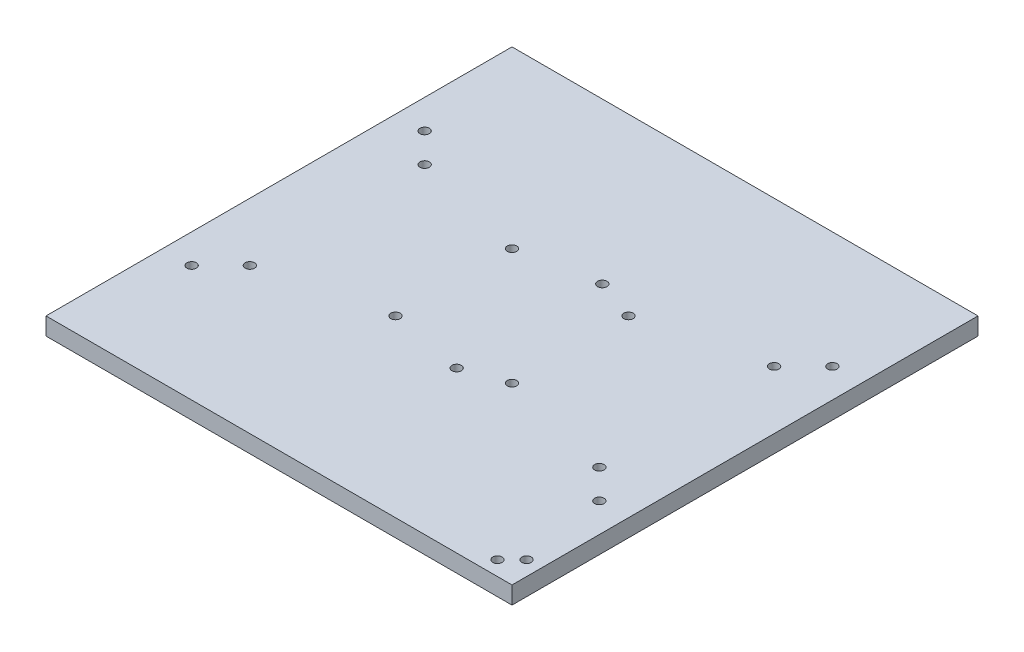
SolidWorks part; units mm, degrees
ref_plane "Alzado" through (0, 0, 0) normal (0, 0, 1) x (1, 0, 0)
ref_plane "Planta" through (0, 0, 0) normal (0, 1, 0) x (1, 0, 0)
ref_plane "Vista lateral" through (0, 0, 0) normal (1, 0, 0) x (0, 0, -1)
sketch "Croquis1" plane through (0, 0, 0) normal (0, 1, 0) x (1, 0, 0)
  line L1 (-80, 80) -> (80, 80)
  line L2 (-80, 80) -> (-80, -80)
  line L3 (-80, -80) -> (80, -80)
  line L4 (80, 80) -> (80, -80)
  line L5 (-80, 80) -> (80, -80) construction
  line L6 (-80, -80) -> (80, 80) construction
  line L7 (-60, 30) -> (60, 30) construction
  line L8 (-60, 30) -> (-60, -30) construction
  line L9 (-60, -30) -> (60, -30) construction
  line L10 (60, 30) -> (60, -30) construction
  line L11 (-60, 30) -> (60, -30) construction
  line L12 (-60, -30) -> (60, 30) construction
  circle A0 centre (-60, 30) radius 1.6193
  circle A1 centre (-60, -30) radius 1.6193
  circle A2 centre (60, -30) radius 1.6193
  circle A3 centre (60, 30) radius 1.6193
  point P0 (0, 0)
  point P6 (0, 0)
  dimension "D5" = 3.2385
  dimension "D1" = 160
  dimension "D2" = 160
  dimension "D3" = 120
  dimension "D4" = 60
extrude "Saliente-Extruir1" add sketch "Croquis1" along normal blind 6
sketch "Croquis5" plane through (0, 6, 0) normal (0, 1, 0) x (1, 0, 0)
  line L1 (-70, 40) -> (70, 40) construction
  line L2 (-70, 40) -> (-70, -40) construction
  line L3 (-70, -40) -> (70, -40) construction
  line L4 (70, 40) -> (70, -40) construction
  line L5 (-70, 40) -> (70, -40) construction
  line L6 (-70, -40) -> (70, 40) construction
  circle A0 centre (-70, 40) radius 1.6193
  circle A1 centre (70, 40) radius 1.6193
  circle A2 centre (70, -40) radius 1.6193
  circle A3 centre (-70, -40) radius 1.6193
  circle A4 centre (-60, 30) radius 1.6193 construction
  point P0 (0, 0)
  dimension "D1" = 140
  dimension "D2" = 80
extrude "Espacio_externo" cut sketch "Croquis5" against normal blind 10
sketch "Croquis6" plane through (0, 6, 0) normal (0, 1, 0) x (1, 0, 0)
  line L1 (-20, 20) -> (20, 20) construction
  line L2 (-20, 20) -> (-20, -20) construction
  line L3 (-20, -20) -> (20, -20) construction
  line L4 (20, 20) -> (20, -20) construction
  line L5 (-20, 20) -> (20, -20) construction
  line L6 (-20, -20) -> (20, 20) construction
  circle A0 centre (-20, 20) radius 1.6193
  circle A1 centre (20, 20) radius 1.6193
  circle A2 centre (20, -20) radius 1.6193
  circle A3 centre (-20, -20) radius 1.6193
  circle A4 centre (-60, 30) radius 1.6193 construction
  point P0 (0, 0)
  dimension "D1" = 40
  dimension "D2" = 40
extrude "Espacio_Centro" cut sketch "Croquis6" against normal blind 10
sketch "Croquis7" plane through (0, 6, 0) normal (0, 1, 0) x (1, 0, 0)
  line L0 (6, 25) -> (6, -25) construction
  circle A0 centre (6, 25) radius 1.6193
  circle A1 centre (6, -25) radius 1.6193
  circle A2 centre (-20, 20) radius 1.6193 construction
  point P2 (6, 0)
  dimension "D1" = 6
  dimension "D2" = 50
extrude "Cortar-Extruir1" cut sketch "Croquis7" against normal blind 10
sketch "Croquis8" plane through (0, 6, 0) normal (0, 1, 0) x (1, 0, 0)
  line L0 (80, -80) -> (80, 80) construction
  line L1 (-80, -80) -> (80, -80) construction
  circle A0 centre (70, -75) radius 1.6193
  circle A1 centre (75, -70) radius 1.6193
  circle A2 centre (70, -40) radius 1.6193 construction
  dimension "D1" = 10
  dimension "D2" = 10
  dimension "D3" = 5
  dimension "D4" = 5
extrude "Cortar-Extruir2" cut sketch "Croquis8" against normal blind 13
